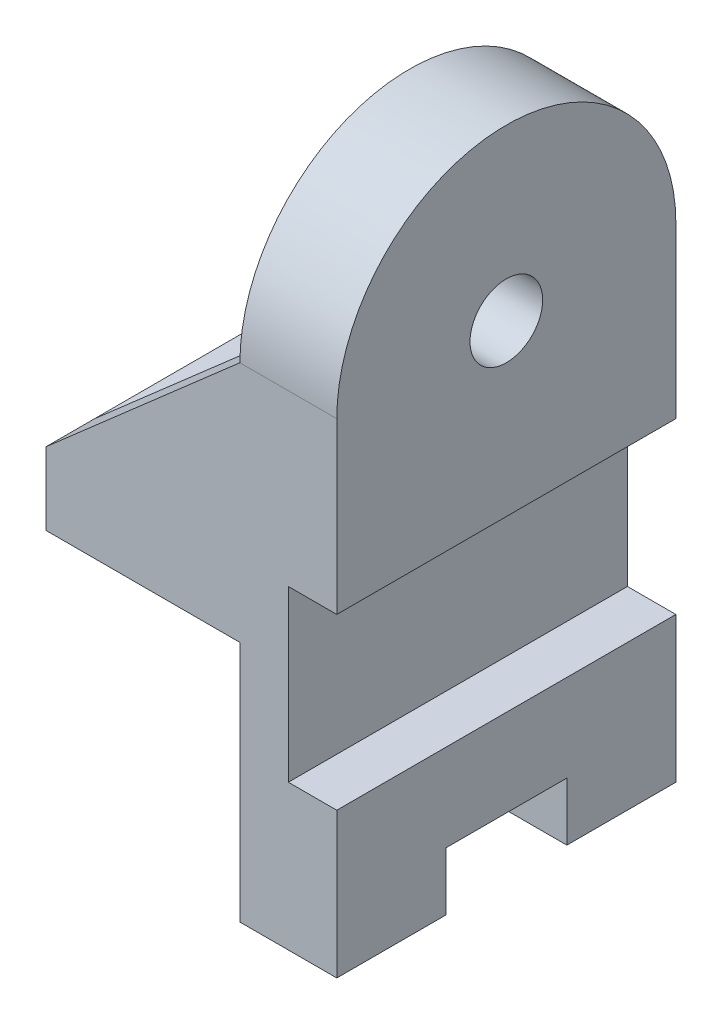
SolidWorks part; units mm, degrees
ref_plane "Спереди" through (0, 0, 0) normal (0, 0, 1) x (1, 0, 0)
ref_plane "Сверху" through (0, 0, 0) normal (0, 1, 0) x (1, 0, 0)
ref_plane "Справа" through (0, 0, 0) normal (1, 0, 0) x (0, 0, -1)
sketch "Эскиз1" plane through (0, 0, 0) normal (1, 0, 0) x (0, 0, -1)
  line L1 (-35, -50) -> (35, -50)
  line L2 (-35, -50) -> (-35, 50)
  line L3 (-35, 50) -> (35, 50)
  line L4 (35, -50) -> (35, 50)
  line L5 (-35, -50) -> (35, 50) construction
  line L6 (-35, 50) -> (35, -50) construction
  line L7 (-12.5, -38) -> (12.5, -38)
  line L8 (-12.5, -38) -> (-12.5, -50)
  line L9 (-12.5, -50) -> (12.5, -50)
  line L10 (12.5, -38) -> (12.5, -50)
  line L11 (-12.5, -38) -> (12.5, -50) construction
  line L12 (-12.5, -50) -> (12.5, -38) construction
  circle A0 centre (0, 50) radius 35
  circle A1 centre (0, 50) radius 7.5
  point P0 (0, 0)
  point P9 (0, -44)
  dimension "D3" = 15
  dimension "D1" = 70
  dimension "D2" = 100
  dimension "D4" = 25
  dimension "D5" = 12
extrude "Бобышка-Вытянуть1" add sketch "Эскиз1" against normal blind 20 contours A0 L2 L1 L8 L7 L10 L4 | A1 L3 A0 | A1 L3 A0
sketch "Эскиз2" plane through (0, 0, -35) normal (0, 0, -1) x (-1, 0, 0)
  line L0 (0, -50) -> (0, 50) construction
  line L1 (10, 15) -> (0, 15)
  line L2 (10, 15) -> (10, -20)
  line L3 (10, -20) -> (0, -20)
  line L4 (0, 15) -> (0, -20)
  line L5 (10, 15) -> (0, -20) construction
  line L6 (10, -20) -> (0, 15) construction
  line L7 (20, -50) -> (0, -50) construction
  line L8 (10, -20) -> (10, -50) construction
  point P0 (5, -2.5)
  dimension "D1" = 30
  dimension "D2" = 35
extrude "Вырез-Вытянуть1" cut sketch "Эскиз2" against normal through all
sketch "Эскиз3" plane through (0, 0, 0) normal (0, 0, 1) x (1, 0, 0)
  line L0 (-20, -50) -> (-20, 50) construction
  line L1 (-20, 15) -> (-60, 15)
  line L2 (-20, 15) -> (-20, 0)
  line L3 (-20, 0) -> (-60, 0)
  line L4 (-60, 15) -> (-60, 0)
  line L5 (-20, -50) -> (0, -50) construction
  dimension "D1" = 40
  dimension "D2" = 15
  dimension "D3" = 50
extrude "Бобышка-Вытянуть2" add sketch "Эскиз3" against normal up to surface and the other way up to surface
sketch "Эскиз4" plane through (0, 0, 0) normal (0, -1, 0) x (1, 0, 0)
  line L0 (-40, -35) -> (-40, 35) construction
  line L1 (-60, -35) -> (-20, -35) construction
  line L2 (-20, 35) -> (-60, 35) construction
  circle A0 centre (-40, 0) radius 6
  dimension "D1" = 12
extrude "Вырез-Вытянуть2" cut sketch "Эскиз4" against normal through all
sketch "Эскиз5" plane through (0, 0, 35) normal (0, 0, 1) x (1, 0, 0)
  line L0 (-60, 15) -> (-20, 50)
  line L1 (-20, 50) -> (-20, 15)
  line L2 (-20, 15) -> (-60, 15)
extrude "Бобышка-Вытянуть3" add sketch "Эскиз5" against normal blind 10
mirror "Зеркальное отражение1" about plane through (0, 0, 0) normal (0, 0, 1) of "Бобышка-Вытянуть3"
